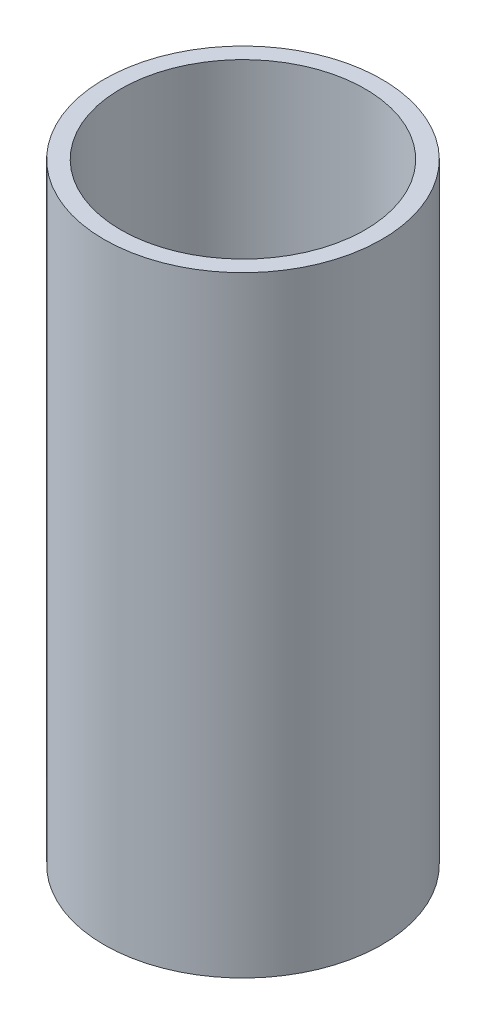
SolidWorks part; units mm, degrees
ref_plane "Front Plane" through (0, 0, 0) normal (0, 0, 1) x (1, 0, 0)
ref_plane "Top Plane" through (0, 0, 0) normal (0, 1, 0) x (1, 0, 0)
ref_plane "Right Plane" through (0, 0, 0) normal (1, 0, 0) x (0, 0, -1)
sketch "Sketch1" plane through (0, 0, 0) normal (0, 1, 0) x (1, 0, 0)
  circle A0 centre (0, 0) radius 12.5
  circle A1 centre (0, 0) radius 11
  dimension "D1" = 25
  dimension "D2" = 22
extrude "Boss-Extrude1" add sketch "Sketch1" along normal blind 55
